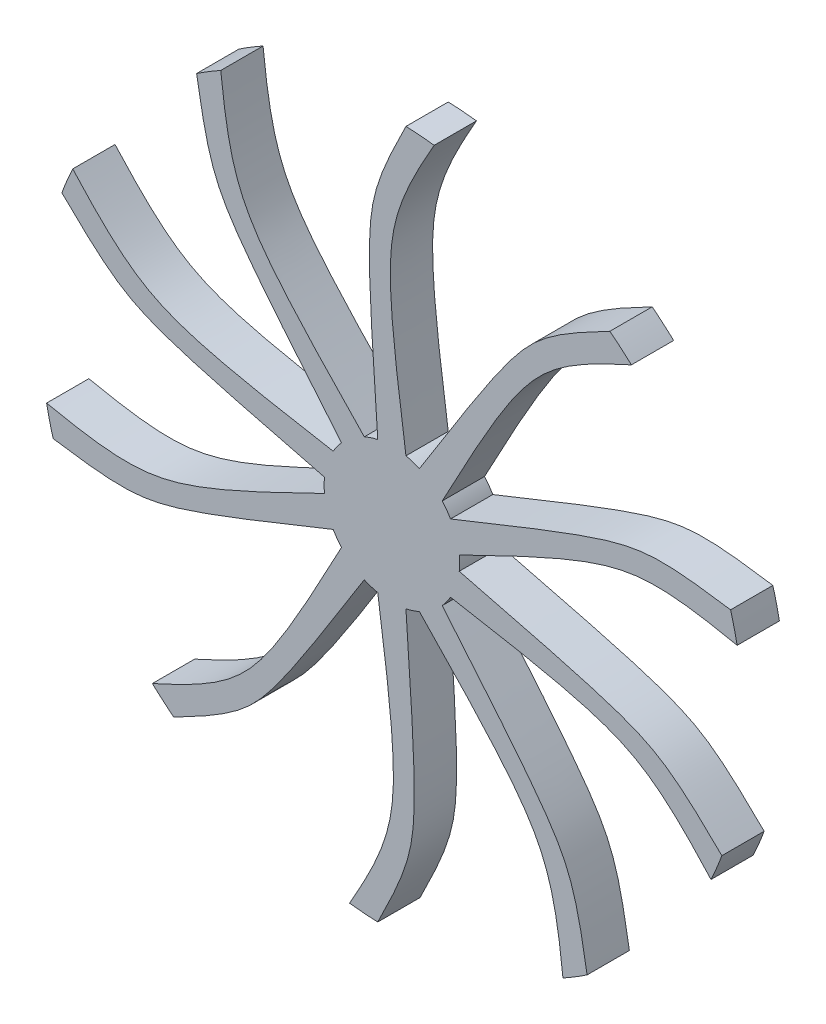
SolidWorks part; units mm, degrees
ref_plane "Front Plane" through (0, 0, 0) normal (0, 0, 1) x (1, 0, 0)
ref_plane "Top Plane" through (0, 0, 0) normal (0, 1, 0) x (1, 0, 0)
ref_plane "Right Plane" through (0, 0, 0) normal (1, 0, 0) x (0, 0, -1)
sketch "Sketch1" plane through (0, 0, 0) normal (0, 0, 1) x (1, 0, 0)
  arc A0 (-10, 47.0181) -> (-19.5464, 43.9163) centre (0, 0) ccw
  arc A1 (30, 247.834) -> (10, 249.4428) centre (0, 0) ccw
  arc A2 (169.9437, 182.8684) -> (154.7089, 195.9256) centre (0, 0) ccw
  arc A3 (244.9746, 48.0532) -> (240.3243, 67.5715) centre (0, 0) ccw
  arc A4 (226.4336, -105.1166) -> (234.144, -86.5926) centre (0, 0) ccw
  arc A5 (121.4027, -218.1355) -> (138.5286, -207.6813) centre (0, 0) ccw
  arc A6 (-30, -247.834) -> (-10, -249.4428) centre (0, 0) ccw
  arc A7 (-169.9437, -182.8684) -> (-154.7089, -195.9256) centre (0, 0) ccw
  arc A8 (-244.9746, -48.0532) -> (-240.3243, -67.5715) centre (0, 0) ccw
  arc A9 (-226.4336, 105.1166) -> (-234.144, 86.5926) centre (0, 0) ccw
  arc A10 (-121.4027, 218.1355) -> (-138.5286, 207.6813) centre (0, 0) ccw
  arc A11 (19.5464, 43.9163) -> (10, 47.0181) centre (0, 0) ccw
  arc A12 (47.807, -5.0188) -> (47.807, 5.0188) centre (0, 0) ccw
  arc A13 (41.6267, 24.0399) -> (35.7267, 32.1606) centre (0, 0) ccw
  arc A14 (35.7267, -32.1606) -> (41.6267, -24.0399) centre (0, 0) ccw
  arc A15 (10, -47.0181) -> (19.5464, -43.9163) centre (0, 0) ccw
  arc A16 (-19.5464, -43.9163) -> (-10, -47.0181) centre (0, 0) ccw
  arc A17 (-41.6267, -24.0399) -> (-35.7267, -32.1606) centre (0, 0) ccw
  arc A18 (-47.807, 5.0188) -> (-47.807, -5.0188) centre (0, 0) ccw
  arc A19 (-35.7267, 32.1606) -> (-41.6267, 24.0399) centre (0, 0) ccw
  conic Q0 (-10, 47.0181) -> (10, 249.4428) control (-20.0701, 189.6678) rho 0.75
  conic Q1 (10, 47.0181) -> (30, 247.834) control (-9.0891, 179.901) rho 0.7
  conic Q2 (35.7267, 32.1606) -> (169.9437, 182.8684) control (98.39, 150.8854) rho 0.7
  conic Q3 (19.5464, 43.9163) -> (154.7089, 195.9256) control (95.2469, 165.2414) rho 0.75
  conic Q4 (47.807, 5.0188) -> (244.9746, 48.0532) control (168.2874, 64.2367) rho 0.7
  conic Q5 (41.6267, 24.0399) -> (240.3243, 67.5715) control (174.1828, 77.6984) rho 0.75
  conic Q6 (41.6267, -24.0399) -> (226.4336, -105.1166) control (173.9047, -46.9483) rho 0.7
  conic Q7 (47.807, -5.0188) -> (234.144, -86.5926) control (186.5868, -39.5228) rho 0.75
  conic Q8 (19.5464, -43.9163) -> (121.4027, -218.1355) control (113.0964, -140.2006) rho 0.7
  conic Q9 (35.7267, -32.1606) -> (138.5286, -207.6813) control (127.721, -141.6476) rho 0.75
  conic Q10 (-10, -47.0181) -> (-30, -247.834) control (9.0891, -179.901) rho 0.7
  conic Q11 (10, -47.0181) -> (-10, -249.4428) control (20.0701, -189.6678) rho 0.75
  conic Q12 (-35.7267, -32.1606) -> (-169.9437, -182.8684) control (-98.39, -150.8854) rho 0.7
  conic Q13 (-19.5464, -43.9163) -> (-154.7089, -195.9256) control (-95.2469, -165.2414) rho 0.75
  conic Q14 (-47.807, -5.0188) -> (-244.9746, -48.0532) control (-168.2874, -64.2367) rho 0.7
  conic Q15 (-41.6267, -24.0399) -> (-240.3243, -67.5715) control (-174.1828, -77.6984) rho 0.75
  conic Q16 (-41.6267, 24.0399) -> (-226.4336, 105.1166) control (-173.9047, 46.9483) rho 0.7
  conic Q17 (-47.807, 5.0188) -> (-234.144, 86.5926) control (-186.5868, 39.5228) rho 0.75
  conic Q18 (-19.5464, 43.9163) -> (-121.4027, 218.1355) control (-113.0964, 140.2006) rho 0.7
  conic Q19 (-35.7267, 32.1606) -> (-138.5286, 207.6813) control (-127.721, 141.6476) rho 0.75
  point P85 (0, 0)
  dimension "D2" = 10
  dimension "D4" = 10
extrude "Boss-Extrude3" add sketch "Sketch1" along normal blind 30
